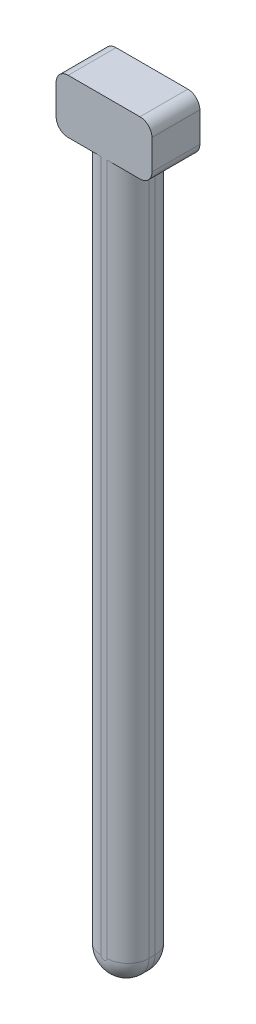
SolidWorks part; units mm, degrees
ref_plane "Front Plane" through (0, 0, 0) normal (0, 0, 1) x (1, 0, 0)
ref_plane "Top Plane" through (0, 0, 0) normal (0, 1, 0) x (1, 0, 0)
ref_plane "Right Plane" through (0, 0, 0) normal (1, 0, 0) x (0, 0, -1)
sketch "Sketch1" plane through (0, 0, 0) normal (0, 0, 1) x (1, 0, 0)
  line L0 (0, 0) -> (0, -60) construction
  line L1 (-4, -2.25) -> (4, -2.25)
  line L2 (-4, -2.25) -> (-4, 2.25)
  line L3 (-4, 2.25) -> (4, 2.25)
  line L4 (4, -2.25) -> (4, 2.25)
  line L5 (-4, -2.25) -> (4, 2.25) construction
  line L6 (-4, 2.25) -> (4, -2.25) construction
  line L7 (-2, 0) -> (-2, -60)
  line L8 (2, 0) -> (2, -60)
  arc A0 (-2, 0) -> (2, 0) centre (0, 0) cw
  arc A1 (-2, -60) -> (2, -60) centre (0, -60) ccw
  point P0 (0, 0)
  dimension "D1" = 60
  dimension "D2" = 4.5
  dimension "D3" = 8
  dimension "D4" = 2
  dimension "D5" = 2
extrude "Boss-Extrude1" add sketch "Sketch1" along normal blind 4 contours L7 A1 L8 L1 | A0 L7 L1 L8 | L7 A0 L8 L1 L4 L3 L2
fillet "Fillet1" radius 1.75 6 edges at (-2, -31.125, 0) (0, -62, 0) (-2, -31.125, 4) (0, -62, 4) (2, -31.125, 0) (2, -31.125, 4)
fillet "Fillet2" radius 1 4 edges at (-4, -2.25, 2) (4, -2.25, 2) (4, 2.25, 2) (-4, 2.25, 2)
